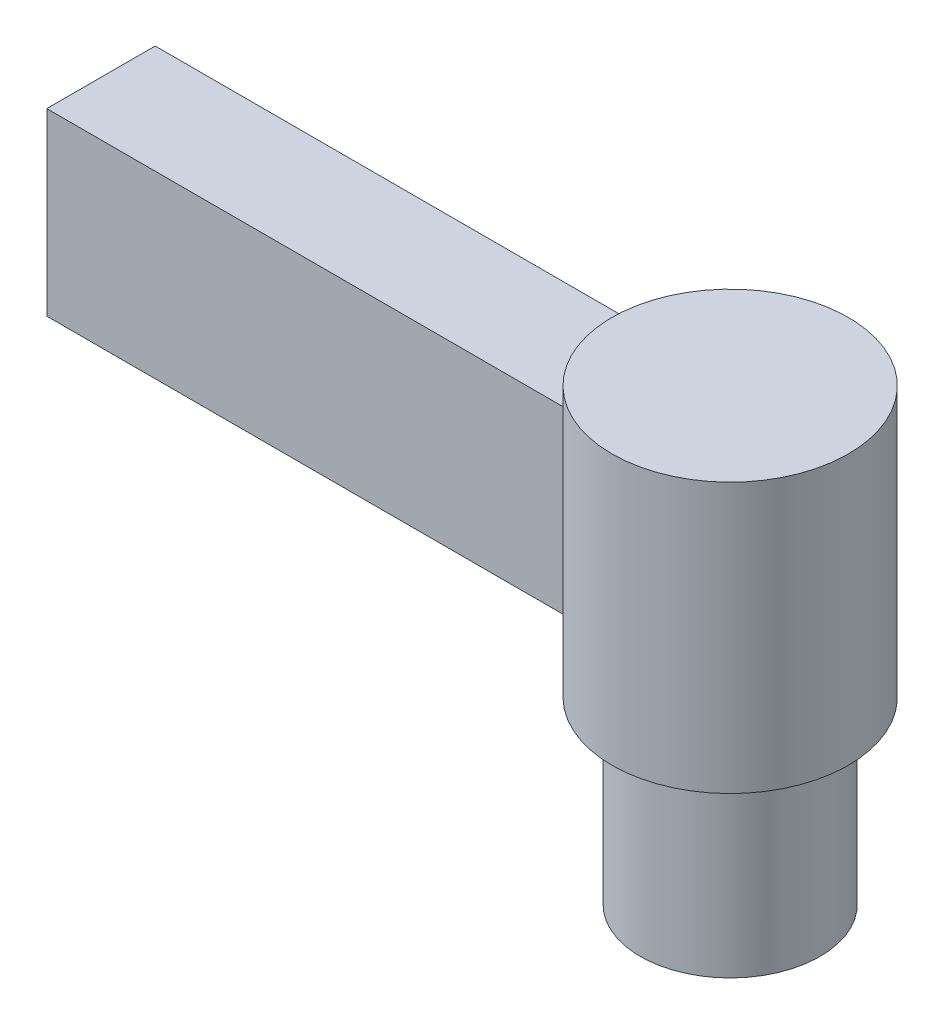
SolidWorks part; units mm, degrees
ref_plane "Front" through (0, 0, 0) normal (0, 0, 1) x (1, 0, 0)
ref_plane "Top" through (0, 0, 0) normal (0, 1, 0) x (1, 0, 0)
ref_plane "Right" through (0, 0, 0) normal (1, 0, 0) x (0, 0, -1)
sketch "Sketch5" plane through (0, 9.3393, 0) normal (0, -1, 0) x (1, 0, 0)
  circle A1 centre (0, 0) radius 1
  dimension "D1" = 2
extrude "Boss-Extrude2" add sketch "Sketch5" along a picked direction on the side against the normal blind 2
sketch "Sketch8" plane through (0, 11.3393, 0) normal (0, 1, 0) x (1, 0, 0)
  circle A0 centre (0, 0) radius 1.3154
extrude "Boss-Extrude4" add sketch "Sketch8" along normal blind 3
sketch "Sketch11" plane through (0, 0, 0) normal (1, 0, 0) x (0, 0, -1)
  line L1 (-0.6031, 11.8104) -> (0.6031, 11.8104)
  line L2 (-0.6031, 11.8104) -> (-0.6031, 13.8104)
  line L3 (-0.6031, 13.8104) -> (0.6031, 13.8104)
  line L4 (0.6031, 11.8104) -> (0.6031, 13.8104)
  line L5 (-0.6031, 11.8104) -> (0.6031, 13.8104) construction
  line L6 (-0.6031, 13.8104) -> (0.6031, 11.8104) construction
  point P0 (0, 12.8104)
  dimension "D1" = 2
extrude "Boss-Extrude5" add sketch "Sketch11" against normal blind 7
